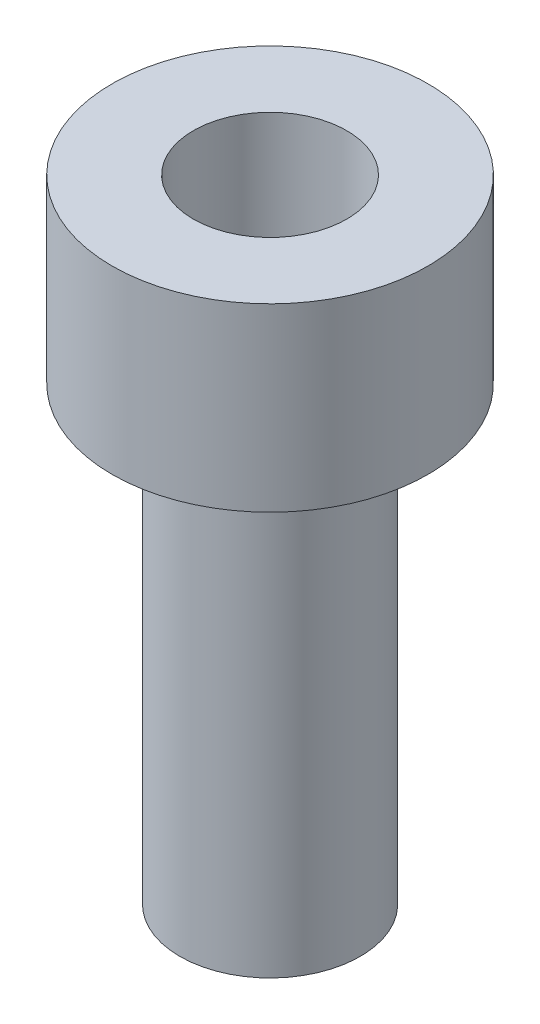
SolidWorks part; units mm, degrees
material "Alloy Steel"
ref_plane "Front Plane" through (0, 0, 0) normal (0, 0, 1) x (1, 0, 0)
ref_plane "Top Plane" through (0, 0, 0) normal (0, 1, 0) x (1, 0, 0)
ref_plane "Right Plane" through (0, 0, 0) normal (1, 0, 0) x (0, 0, -1)
other "Configuration Table"
sketch "Sketch1" plane through (0, 0, 0) normal (0, 1, 0) x (1, 0, 0)
  circle A0 centre (0, 0) radius 3.5
  dimension "D1" = 7
extrude "Head" add sketch "Sketch1" along normal blind 4
sketch "Sketch2" plane through (0, 0, 0) normal (0, 1, 0) x (1, 0, 0)
  circle A0 centre (0, 0) radius 2
  dimension "D1" = 4
extrude "Shank" add sketch "Sketch2" along normal blind 10 from offset 10
sketch "Sketch3" plane through (0, 0, 0) normal (0, 1, 0) x (1, 0, 0)
  circle A0 centre (0, 0) radius 1.7
  dimension "D1" = 3.4
extrude "Socket" cut sketch "Sketch3" against normal blind 2.4 from offset 4
equation "\"Jar_OD\"= 90  'ASSUMED - Part G fallback - jar outer diameter"
equation "\"Jar_H\"= 120  'ASSUMED - Part G fallback - jar height"
equation "\"Pump_L\"= 45  'ASSUMED - Part G fallback"
equation "\"Pump_W\"= 24  'ASSUMED - Part G fallback"
equation "\"Pump_H\"= 33  'ASSUMED - Part G fallback"
equation "\"Pump_Outlet_OD\"= 7.5  'ASSUMED - Part G fallback"
equation "\"Tube_OD\"= 8  'ASSUMED - Part G fallback"
equation "\"Tube_ID\"= 6  'ASSUMED - Part G fallback"
equation "\"TDS_Body_Dia\"= 12  'ASSUMED - Part G fallback"
equation "\"TDS_Wet_Len\"= 45  'ASSUMED - Part G fallback - length in water"
equation "\"DS_Tube_Dia\"= 6  'ASSUMED - Part G fallback"
equation "\"DS_Tube_Len\"= 50  'ASSUMED - Part G fallback"
equation "\"ORP_Body_Dia\"= 12  'ASSUMED - Part G fallback"
equation "\"ORP_Body_Len\"= 150  'ASSUMED - Part G fallback"
equation "\"ORP_Cap_Dia\"= 16  'ASSUMED - Part G fallback"
equation "\"Turb_W\"= 33  'ASSUMED - Part G fallback - head width"
equation "\"Turb_D\"= 28  'ASSUMED - Part G fallback - head depth"
equation "\"Turb_H\"= 30  'ASSUMED - Part G fallback - head height"
equation "\"Turb_Slot_W\"= 10  'ASSUMED - Part G fallback - slot width"
equation "\"Flow_L\"= 62  'ASSUMED - Part G fallback YF-S201"
equation "\"Flow_W\"= 36  'ASSUMED - Part G fallback"
equation "\"Flow_H\"= 35  'ASSUMED - Part G fallback"
equation "\"Thread_G12_OD\"= 20.955  'ASSUMED - Part G fallback thread G1/2 (major diameter)"
equation "\"Valve_L\"= 75  'ASSUMED - Part G fallback"
equation "\"Valve_W\"= 45  'ASSUMED - Part G fallback"
equation "\"Valve_H\"= 60  'ASSUMED - Part G fallback"
equation "\"Tee_L\"= 40  'ASSUMED - Part G fallback - overall length"
equation "\"Tee_Branch_L\"= 25  'ASSUMED - Part G fallback"
equation "\"Tee_OD\"= 12  'ASSUMED - Part G fallback"
equation "\"Cuv_W\"= 12.5  'ASSUMED - old R3 cuvette (station suppressed in SS4)"
equation "\"Cuv_D\"= 12.5  'ASSUMED - old R3 cuvette (station suppressed in SS4)"
equation "\"Cuv_H\"= 45  'ASSUMED - old R3 cuvette (station suppressed in SS4)"
equation "\"LED_Board_L\"= 20  'ASSUMED - Part G fallback"
equation "\"LED_Board_W\"= 20  'ASSUMED - Part G fallback - LED at centre"
equation "\"GUVA_L\"= 20  'ASSUMED - Part G fallback"
equation "\"GUVA_W\"= 12  'ASSUMED - Part G fallback - sensor at centre"
equation "\"Reed_L\"= 27  'ASSUMED - Part G fallback MC-38 half"
equation "\"Reed_W\"= 14  'ASSUMED - Part G fallback"
equation "\"Reed_H\"= 8  'ASSUMED - Part G fallback"
equation "\"ESP_L\"= 51  'ASSUMED - Part G fallback"
equation "\"ESP_W\"= 28  'ASSUMED - Part G fallback"
equation "\"TFT_L\"= 58  'ASSUMED - Part G fallback - board"
equation "\"TFT_W\"= 35  'ASSUMED - Part G fallback - board"
equation "\"TFT_Win_L\"= 35  'ASSUMED - Part G fallback - visible window"
equation "\"TFT_Win_W\"= 28  'ASSUMED - Part G fallback - visible window"
equation "\"Relay_L\"= 50  'ASSUMED - Part G fallback"
equation "\"Relay_W\"= 26  'ASSUMED - Part G fallback"
equation "\"Relay_H\"= 19  'ASSUMED - Part G fallback"
equation "\"Mosfet_L\"= 34  'ASSUMED - Part G fallback"
equation "\"Mosfet_W\"= 17  'ASSUMED - Part G fallback"
equation "\"Mosfet_H\"= 12  'ASSUMED - Part G fallback"
equation "\"TDS_Board_L\"= 42  'ASSUMED - Part G fallback"
equation "\"TDS_Board_W\"= 32  'ASSUMED - Part G fallback"
equation "\"Turb_Board_L\"= 38  'ASSUMED - Part G fallback"
equation "\"Turb_Board_W\"= 28  'ASSUMED - Part G fallback"
equation "\"BNC_Thread_Dia\"= 9.5  'ASSUMED - Part G fallback"
equation "\"Plate_L\"= 420  'ASSUMED - Part G fallback"
equation "\"Plate_W\"= 297  'ASSUMED - Part G fallback"
equation "\"Plate_T\"= 6  'ASSUMED - Part G fallback"
equation "\"Probe_Clr\"= 0.3  'DESIGN VALUE - Part C rule 3 - printed probe hole = diameter + 0.3"
equation "\"Cuv_Clr\"= 0.2  'DESIGN VALUE - Part C rule 3 - cuvette pocket = size + 0.2"
equation "\"Label_H\"= 0.6  'DESIGN VALUE - Part D - raised label height"
equation "\"Booster_L\"= 150  'ASSUMED - Part G fallback - booster pump"
equation "\"Booster_W\"= 95  'ASSUMED - Part G fallback"
equation "\"Booster_H\"= 100  'ASSUMED - Part G fallback"
equation "\"PTube_OD\"= 6.35  'ASSUMED - Part G fallback - product tube 1/4 inch"
equation "\"Qz_Out\"= 12  'ASSUMED - Part G fallback - quartz channel outside square"
equation "\"Qz_Path\"= 10  'ASSUMED - Part G fallback - quartz channel inside light path"
equation "\"Qz_L\"= 40  'ASSUMED - Part G fallback - quartz channel length"
equation "\"LED860_Dia\"= 5  'ASSUMED - Part G fallback - 860 nm LED"
equation "\"BPW_L\"= 5.4  'ASSUMED - Part G fallback - BPW34"
equation "\"BPW_W\"= 4.3  'ASSUMED - Part G fallback - BPW34"
equation "\"Cart_Dia\"= 50  'ASSUMED - Part G fallback - sediment and pre-carbon cartridges"
equation "\"Cart_L\"= 255  'ASSUMED - Part G fallback"
equation "\"UF_Dia\"= 50  'ASSUMED - Part G fallback - UF cartridge"
equation "\"UF_L\"= 260  'ASSUMED - Part G fallback"
equation "\"RO_Dia\"= 62  'ASSUMED - Part G fallback - RO membrane housing"
equation "\"RO_L\"= 300  'ASSUMED - Part G fallback"
equation "\"UVC_Dia\"= 40  'ASSUMED - Part G fallback - UV-C chamber"
equation "\"UVC_L\"= 300  'ASSUMED - Part G fallback"
equation "\"Tank_W\"= 260  'ASSUMED - Part G fallback - storage tank"
equation "\"Tank_D\"= 160  'ASSUMED - Part G fallback"
equation "\"Tank_H\"= 300  'ASSUMED - Part G fallback"
equation "\"Cab_W\"= 400  'ASSUMED - Part G fallback - purifier cabinet"
equation "\"Cab_D\"= 270  'ASSUMED - Part G fallback"
equation "\"Cab_H\"= 560  'ASSUMED - Part G fallback"
equation "\"ORP_Board_L\"= 40  'ASSUMED - Part G fallback - ORP buffer board"
equation "\"ORP_Board_W\"= 30  'ASSUMED - Part G fallback"
equation "\"Opt_Board_L\"= 50  'ASSUMED - Part G fallback - optical front-end board"
equation "\"Opt_Board_W\"= 40  'ASSUMED - Part G fallback"
equation "\"Buck_L\"= 43  'ASSUMED - Part G fallback - 12 V to 5 V buck module"
equation "\"Buck_W\"= 21  'ASSUMED - Part G fallback"
equation "\"Buck_H\"= 14  'ASSUMED - Part G fallback"
equation "\"BB_L\"= 165  'ASSUMED - Part G fallback - breadboard (As_Built_R3 only)"
equation "\"BB_W\"= 55  'ASSUMED - Part G fallback"
equation "\"BB_H\"= 10  'ASSUMED - Part G fallback"
